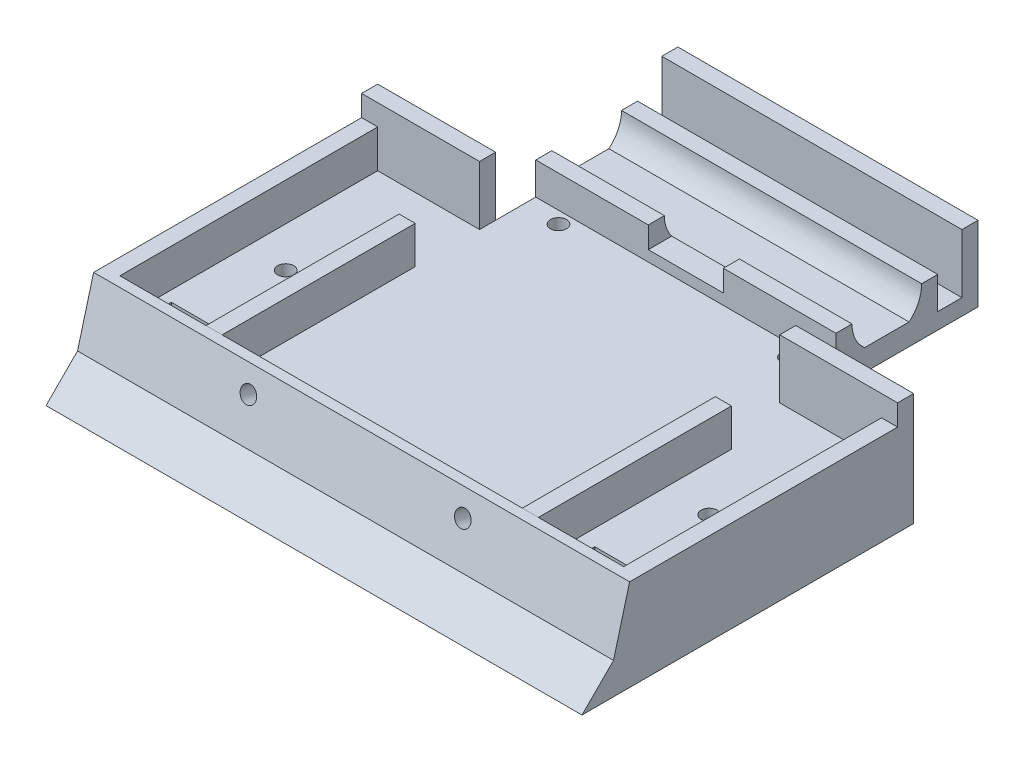
SolidWorks part; units mm, degrees
ref_plane "Plano frontal" through (0, 0, 0) normal (0, 0, 1) x (1, 0, 0)
ref_plane "Plano superior" through (0, 0, 0) normal (0, 1, 0) x (1, 0, 0)
ref_plane "Plano direito" through (0, 0, 0) normal (1, 0, 0) x (0, 0, -1)
sketch "Esboço1" plane through (0, 0, 0) normal (1, 0, 0) x (0, 0, -1)
  line L1 (0, 0) -> (90, 0)
  line L2 (0, 0) -> (0, 10)
  line L3 (0, 10) -> (90, 10)
  line L4 (90, 0) -> (90, 10)
  dimension "D1" = 10
  dimension "D2" = 90
extrude "Ressalto-extrusão1" add sketch "Esboço1" along normal blind 100
sketch "Esboço3" plane through (0, 0, -90) normal (0, 0, -1) x (-1, 0, 0)
  line L0 (-93, 0) -> (-93, 2)
  line L1 (-100, 0) -> (0, 0) construction
  line L2 (-93, 2) -> (-97, 2)
  line L3 (-97, 2) -> (-97, 7)
  line L4 (-97, 7) -> (-3, 7)
  line L5 (-3, 7) -> (-3, 2)
  line L6 (-3, 2) -> (-7, 2)
  line L7 (-7, 2) -> (-7, 0)
  line L10 (0, 0) -> (0, 10) construction
  line L11 (-93, 0) -> (-7, 0)
  dimension "D1" = 94
  dimension "D2" = 3
  dimension "D3" = 5
  dimension "D4" = 2
  dimension "D5" = 4
  dimension "D6" = 4
  dimension "D7" = 2
extrude "Corte-extrusão1" cut sketch "Esboço3" against normal blind 73
sketch "Esboço5" plane through (0, 10, 0) normal (0, 1, 0) x (1, 0, 0)
  line L0 (100, 0) -> (0, 0) construction
  line L1 (5, 6) -> (16, 6)
  line L2 (5, 6) -> (5, 12.5)
  line L3 (5, 12.5) -> (16, 12.5)
  line L4 (16, 6) -> (16, 12.5)
  line L5 (84, 6) -> (95, 6)
  line L6 (84, 6) -> (84, 12.5)
  line L7 (84, 12.5) -> (95, 12.5)
  line L8 (95, 6) -> (95, 12.5)
  line L9 (0, 90) -> (0, 0) construction
  line L10 (100, 90) -> (100, 0) construction
  dimension "D1" = 6.5
  dimension "D2" = 6.5
  dimension "D3" = 11
  dimension "D4" = 11
  dimension "D5" = 6
  dimension "D6" = 6
  dimension "D7" = 5
  dimension "D8" = 5
extrude "Corte-extrusão2" cut sketch "Esboço5" against normal through all
sketch "Esboço8" plane through (0, 0, -17) normal (0, 0, -1) x (-1, 0, 0)
  line L1 (-97, 2) -> (-3, 2)
  line L2 (-97, 2) -> (-97, 7)
  line L3 (-97, 7) -> (-3, 7)
  line L4 (-3, 2) -> (-3, 7)
extrude "Corte-extrusão3" cut sketch "Esboço8" against normal blind 3
sketch "Esboço9" plane through (0, 10, 0) normal (0, 1, 0) x (1, 0, 0)
  line L0 (100, 90) -> (0, 90) construction
  line L1 (0, 0) -> (2, 0)
  line L2 (0, 0) -> (0, 90)
  line L5 (100, 90) -> (100, 0) construction
  line L6 (0, 0) -> (100, 0)
  line L7 (0, 0) -> (0, 1.6783)
  line L8 (3, 3) -> (97, 3)
  line L9 (100, 0) -> (100, 1.6783)
  line L10 (3, 90) -> (3, 3)
  line L12 (100, 1.6783) -> (100, 90)
  line L13 (100, 90) -> (97, 90)
  line L14 (97, 3) -> (97, 87)
  line L15 (3, 90) -> (97, 90)
  line L17 (3, 87) -> (97, 87)
  dimension "D1" = 3
  dimension "D2" = 3
  dimension "D3" = 3
  dimension "D4" = 3
  dimension "D5" = 3
extrude "Ressalto-extrusão2" add sketch "Esboço9" along normal blind 8
sketch "Esboço10" plane through (0, 0, 0) normal (-1, 0, 0) x (0, 0, 1)
  line L0 (-90, 18) -> (0, 18) construction
  line L1 (-90, 0) -> (-56, 0)
  line L2 (-90, 0) -> (-90, 18)
  line L3 (-90, 18) -> (-56, 18)
  line L4 (-56, 0) -> (-56, 18)
  dimension "D1" = 34
extrude "Corte-extrusão4" cut sketch "Esboço10" against normal blind 22
sketch "Esboço11" plane through (100, 0, 0) normal (1, 0, 0) x (0, 0, -1)
  line L0 (0, 18) -> (90, 18) construction
  line L1 (90, 0) -> (56, 0)
  line L2 (90, 0) -> (90, 18)
  line L3 (90, 18) -> (56, 18)
  line L4 (56, 0) -> (56, 18)
  dimension "D1" = 34
extrude "Corte-extrusão5" cut sketch "Esboço11" against normal blind 22
sketch "Esboço15" plane through (100, 0, 0) normal (1, 0, 0) x (0, 0, -1)
  line L0 (0, 5.8843) -> (3.2464, 18)
  line L1 (0, 5.8843) -> (4.0032, 20.8244) construction
  line L2 (0, 18) -> (56, 18) construction
  line L3 (3.2464, 18) -> (0, 18)
  line L4 (0, 18) -> (0, 5.8843)
extrude "Corte-extrusão8" cut sketch "Esboço15" against normal blind 100
sketch "Esboço19" plane through (100, 0, 0) normal (1, 0, 0) x (0, 0, -1)
  line L1 (3, 17.0804) -> (56, 17.0804)
  line L2 (3, 17.0804) -> (3, 18)
  line L3 (3, 18) -> (56, 18)
  line L4 (56, 17.0804) -> (56, 18)
extrude "Corte-extrusão10" cut sketch "Esboço19" against normal through all
sketch "Esboço20" plane through (78, 0, 0) normal (1, 0, 0) x (0, 0, -1)
  line L1 (87, 10) -> (56, 10) construction
  line L10 (68.8396, 11) -> (77.1372, 11)
  line L13 (63.4884, 10) -> (81.8305, 10)
  line L15 (82.4884, 13) -> (82.4884, 10)
  line L16 (82.4884, 10) -> (81.8305, 10)
  line L22 (82.4884, 14) -> (82.4884, 13)
  line L23 (63.4884, 14) -> (63.4884, 10)
  line L25 (82.4884, 14) -> (82.4884, 16.0037)
  line L26 (82.4884, 16.0037) -> (79.4884, 16.0037)
  line L28 (63.4884, 14) -> (63.4884, 16.0037)
  line L29 (63.4884, 16.0037) -> (66.4884, 16.0037)
  arc A0 (66.4884, 16.0037) -> (68.8396, 11) centre (72.9884, 16.0037) ccw
  arc A1 (77.1372, 11) -> (79.4884, 16.0037) centre (72.9884, 16.0037) ccw
  dimension "D3" = 1
extrude "Ressalto-extrusão4" add sketch "Esboço20" against normal blind 56
sketch "Esboço21" plane through (78, 0, 0) normal (1, 0, 0) x (0, 0, -1)
  line L1 (87, 18) -> (90, 18)
  line L2 (87, 18) -> (87, 21)
  line L3 (87, 21) -> (90, 21)
  line L4 (90, 18) -> (90, 21)
extrude "Ressalto-extrusão5" add sketch "Esboço21" against normal blind 56
sketch "Esboço22" plane through (100, 0, 0) normal (1, 0, 0) x (0, 0, -1)
  line L6 (4.899, 17.0804) -> (3, 10)
  line L7 (3, 17.0804) -> (3, 10)
  line L8 (3, 17.0804) -> (4.899, 17.0804)
  line L9 (3, 17.0804) -> (56, 17.0804) construction
extrude "Ressalto-extrusão6" add sketch "Esboço22" against normal blind 100
sketch "Esboço25" plane through (0, 10, 0) normal (0, 1, 0) x (1, 0, 0)
  line L1 (89.5, 28.3354) -> (91, 28.3354)
  line L3 (91, 28.3354) -> (89.5, 28.3354)
  circle A0 centre (10.5, 28.3354) radius 1.5
  circle A1 centre (89.5, 28.3354) radius 1.5
  dimension "D2" = 3
extrude "Corte-extrusão11" cut sketch "Esboço25" against normal through all contours A0 | L1 L3
sketch "Esboço26" plane through (0, 10, 0) normal (0, 1, 0) x (1, 0, 0)
  circle A0 centre (89.5, 28.3354) radius 1.5
  dimension "D2" = 3
extrude "Corte-extrusão14" cut sketch "Esboço26" against normal through all
sketch "Esboço28" plane through (0, 10, 0) normal (0, 1, 0) x (1, 0, 0)
  line L5 (3, 4.899) -> (97, 4.899) construction
  line L10 (22, 56) -> (19, 56)
  line L11 (22, 56) -> (22, 4.899)
  line L12 (22, 4.899) -> (19, 4.899)
  line L13 (19, 56) -> (19, 4.899)
  line L14 (78, 63.4884) -> (78, 56) construction
  line L15 (78, 56) -> (81, 56)
  line L16 (78, 56) -> (78, 4.899)
  line L17 (78, 4.899) -> (81, 4.899)
  line L18 (81, 56) -> (81, 4.899)
  dimension "D1" = 3
  dimension "D2" = 3
extrude "Ressalto-extrusão7" add sketch "Esboço28" along normal blind 7
sketch "Esboço29" plane through (81, 0, 0) normal (1, 0, 0) x (0, 0, -1)
  line L0 (4.899, 10) -> (3, 10)
  line L1 (3, 10) -> (4.899, 17.0804)
  line L2 (4.899, 17.0804) -> (4.899, 10)
extrude "Ressalto-extrusão8" add sketch "Esboço29" against normal blind 62
sketch "Esboço30" plane through (0, 17, 0) normal (0, 1, 0) x (1, 0, 0)
  line L0 (3, 4.899) -> (3, 56) construction
  line L1 (19, 56) -> (3, 56)
  line L2 (19, 56) -> (19, 53)
  line L3 (19, 53) -> (3, 53)
  line L4 (3, 56) -> (3, 53)
  line L5 (97, 56) -> (97, 4.899) construction
  line L6 (81, 56) -> (97, 56)
  line L7 (81, 56) -> (81, 53)
  line L8 (81, 53) -> (97, 53)
  line L9 (97, 56) -> (97, 53)
  dimension "D1" = 3
  dimension "D2" = 3
extrude "Ressalto-extrusão9" add sketch "Esboço30" against normal blind 7
sketch "Esboço31" plane through (0, 17, 0) normal (0, 1, 0) x (1, 0, 0)
  line L0 (81, 4.899) -> (81, 53) construction
  line L1 (19, 53) -> (81, 53)
  line L2 (19, 53) -> (19, 41)
  line L3 (19, 41) -> (81, 41)
  line L4 (81, 53) -> (81, 41)
  dimension "D1" = 12
extrude "Corte-extrusão15" cut sketch "Esboço31" against normal blind 7
sketch "Esboço33" plane through (100, 0, 0) normal (1, 0, 0) x (0, 0, -1)
  line L0 (5.9502, 21) -> (56, 21) construction
  line L1 (56, 17.0804) -> (53, 17.0804)
  line L2 (56, 17.0804) -> (56, 21)
  line L3 (56, 21) -> (53, 21)
  line L4 (53, 17.0804) -> (53, 21)
  dimension "D1" = 3
extrude "Ressalto-extrusão11" add sketch "Esboço33" against normal blind 22
sketch "Esboço34" plane through (0, 0, 0) normal (-1, 0, 0) x (0, 0, 1)
  line L1 (-56, 21) -> (-53, 21)
  line L2 (-56, 21) -> (-56, 17.0804)
  line L3 (-56, 17.0804) -> (-53, 17.0804)
  line L4 (-53, 21) -> (-53, 17.0804)
extrude "Ressalto-extrusão12" add sketch "Esboço34" against normal blind 22
sketch "Esboço35" plane through (0, 0, -56) normal (0, 0, -1) x (-1, 0, 0)
  line L0 (-97, 17) -> (-78, 17) construction
  line L1 (-3, 17.0804) -> (-22, 17.0804)
  line L2 (-3, 17.0804) -> (-3, 17)
  line L3 (-3, 17) -> (-22, 17)
  line L4 (-22, 17.0804) -> (-22, 17)
  line L5 (-97, 17.0804) -> (-78, 17.0804)
  line L6 (-97, 17.0804) -> (-97, 17)
  line L7 (-97, 17) -> (-78, 17)
  line L8 (-78, 17.0804) -> (-78, 17)
  line L9 (-78, 17) -> (-78, 10) construction
extrude "Ressalto-extrusão13" add sketch "Esboço35" against normal blind 3
sketch "Esboço36" plane through (0, 10, 0) normal (0, 1, 0) x (1, 0, 0)
  circle A0 centre (71.5, 61.2334) radius 1.5
  circle A1 centre (28.5, 61.2334) radius 1.5
  circle A2 centre (71.5, 84.7434) radius 1.5
  circle A3 centre (28.5, 84.7434) radius 1.5
  dimension "D1" = 3
  dimension "D2" = 3
  dimension "D3" = 3
  dimension "D4" = 3
extrude "Corte-extrusão16" cut sketch "Esboço36" against normal through all
sketch "Esboço37" plane through (0, 0, -63.4884) normal (0, 0, 1) x (1, 0, 0)
  line L5 (43, 16.0037) -> (57, 16.0037)
  line L6 (43, 16.0037) -> (43, 12.0037)
  line L7 (43, 12.0037) -> (57, 12.0037)
  line L8 (57, 16.0037) -> (57, 12.0037)
  dimension "D3" = 14
extrude "Corte-extrusão17" cut sketch "Esboço37" against normal blind 6
sketch "Esboço38" plane through (100, 0, 0) normal (1, 0, 0) x (0, 0, -1)
  line L0 (0, 0) -> (-5.8843, 0)
  line L1 (-5.8843, 0) -> (0, 5.8843)
  line L2 (0, 5.8843) -> (0, 0)
extrude "Ressalto-extrusão14" add sketch "Esboço38" against normal through all
sketch "Esboço39" plane through (0, 0.3942, 1.4711) normal (0, 0.2588, 0.9659) x (1, 0, 0)
  circle A0 centre (30, 12.9507) radius 1.5
  circle A1 centre (70, 12.9507) radius 1.5
extrude "Corte-extrusão18" cut sketch "Esboço39" against normal blind 4
sketch "Esboço40" plane through (0, 0, 0) normal (0, -1, 0) x (1, 0, 0)
  circle A0 centre (28.5, -10.2334) radius 1.5
  circle A1 centre (71.5, -10.2334) radius 1.5
  dimension "D1" = 3
  dimension "D2" = 3
extrude "Corte-extrusão19" cut sketch "Esboço40" against normal blind 10
sketch "Esboço42" plane through (0, 0, -14) normal (0, 0, -1) x (-1, 0, 0)
  line L0 (-3, 7) -> (-97, 7) construction
  line L1 (-97, 2) -> (-3, 2) construction
  line L2 (-77.5, 7) -> (-22.5, 7)
  line L3 (-77.5, 7) -> (-77.5, 2)
  line L5 (-22.5, 7) -> (-22.5, 2)
  line L7 (-93, 0) -> (-7, 0) construction
  line L9 (-77.5, 2) -> (-77.5, 0)
  line L10 (-77.5, 0) -> (-22.5, 0)
  line L11 (-22.5, 2) -> (-22.5, 0)
  dimension "D1" = 55
  dimension "D2" = 22.5
extrude "Corte-extrusão21" cut sketch "Esboço42" against normal blind 7
sketch "Esboço43" plane through (0, 0, 0) normal (0, -1, 0) x (1, 0, 0)
  line L11 (22.5, -7) -> (77.5, -7)
  line L12 (22.5, -7) -> (22.5, -21.1963)
  line L13 (22.5, -21.1963) -> (77.5, -21.1963)
  line L14 (77.5, -7) -> (77.5, -21.1963)
  dimension "D1" = 55
extrude "Corte-extrusão23" cut sketch "Esboço43" against normal blind 2
